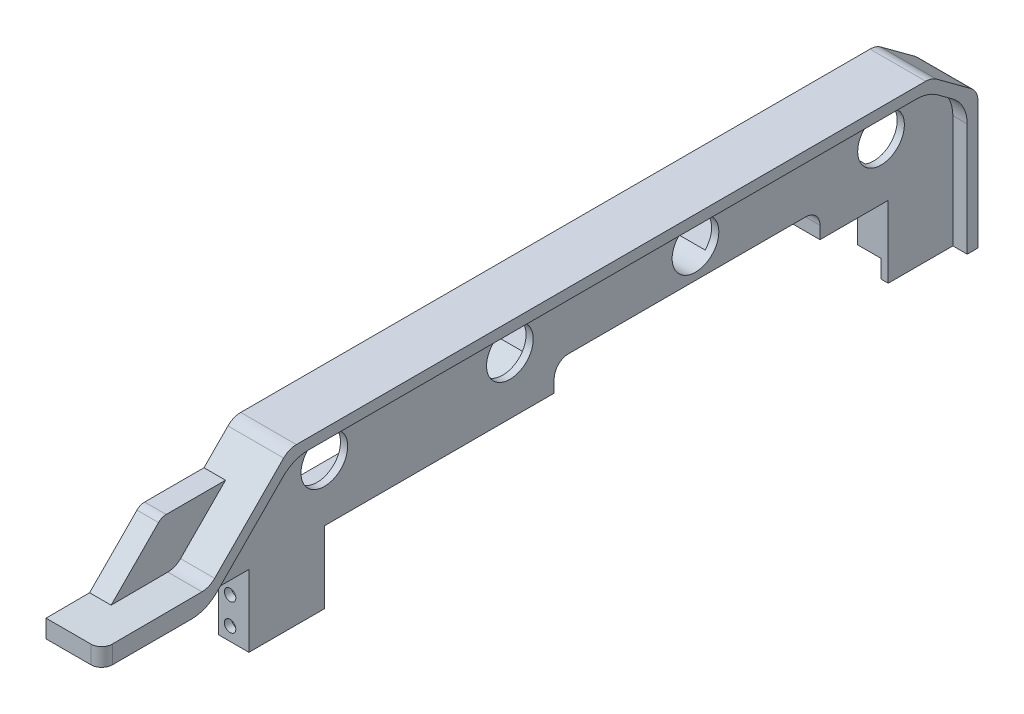
SolidWorks part; units mm, degrees
ref_plane "Front Plane" through (0, 0, 0) normal (0, 0, 1) x (1, 0, 0)
ref_plane "Top Plane" through (0, 0, 0) normal (0, 1, 0) x (1, 0, 0)
ref_plane "Right Plane" through (0, 0, 0) normal (1, 0, 0) x (0, 0, -1)
sketch "Sketch1" plane through (0, 0, 0) normal (1, 0, 0) x (0, 0, -1)
  line L0 (0, 0) -> (-130, 0)
  line L1 (0, 0) -> (74, 0) construction
  line L2 (0, 0) -> (0, 7.5)
  line L3 (0, 7.5) -> (74, 7.5)
  line L4 (74, 7.5) -> (74, 0)
  line L5 (74, 0) -> (114, 0)
  line L6 (-130, 0) -> (-130, 5)
  line L7 (-130, 5) -> (-100.0004, 5.1483)
  line L8 (-100.0004, 5.1483) -> (-77.8685, 27.5)
  line L9 (114, 0) -> (114, 18)
  line L10 (114, 18) -> (101.0882, 27.5)
  line L11 (101.0882, 27.5) -> (-77.8685, 27.5)
  dimension "D1" = 130
  dimension "D2" = 74
  dimension "D3" = 7.5
  dimension "D4" = 40
  dimension "D5" = 30
  dimension "D6" = 5
  dimension "D7" = 135
  dimension "D8" = 20
  dimension "D9" = 18
extrude "Boss-Extrude1" add sketch "Sketch1" along normal blind 25
sketch "Sketch4" plane through (25, 0, 0) normal (1, 0, 0) x (0, 0, -1)
  line L11 (-130, 0) -> (0, 0) construction
  line L12 (-130, 0) -> (0, 0) construction
  line L13 (-100.8762, 0) -> (0, 0)
  line L14 (0, 0) -> (111, 0)
  line L15 (74, 0) -> (114, 0) construction
  line L16 (111, 0) -> (111, 3)
  line L22 (-3, 3) -> (-3, 10.5)
  line L23 (-3, 10.5) -> (77, 10.5)
  line L24 (77, 10.5) -> (77, 3)
  line L25 (77, 3) -> (111, 3)
  line L26 (111, 3) -> (111, 16.4828)
  line L27 (111, 16.4828) -> (100.1035, 24.5)
  line L28 (100.1035, 24.5) -> (-76.6172, 24.5)
  line L29 (-76.6172, 24.5) -> (-97.9057, 3)
  line L30 (-97.9057, 3) -> (-3, 3)
  line L35 (111, 3) -> (111, 16.4828)
  line L36 (111, 16.4828) -> (100.1035, 24.5)
  line L37 (100.1035, 24.5) -> (-76.6172, 24.5)
  line L38 (-76.6172, 24.5) -> (-100.8762, 0)
  dimension "D1" = 3
extrude "Cut-Extrude1" cut sketch "Sketch4" against normal blind 4
ref_plane "Plane1" through (12.5, 0, 0) normal (1, 0, 0) x (0, 0, -1)
mirror "Mirror2" about plane through (12.5, 0, 0) normal (1, 0, 0) of "Cut-Extrude1"
fillet "Fillet1" radius 4 2 edges at (12.5, 7.5, -74) (12.5, 7.5, 0)
fillet "Fillet2" radius 10 8 edges at (23, 16.4828, -111) (23, 24.5, -100.1035) (2, 16.4828, -111) (2, 24.5, -100.1035) (2, 24.5, 76.6172) (23, 24.5, 76.6172) (2, 0, 100.8762) (23, 0, 100.8762)
fillet "Fillet3" radius 5 4 edges at (12.5, 18, -114) (12.5, 27.5, -101.0882) (12.5, 27.5, 77.8685) (12.5, 5.1483, 100.0004)
fillet "Fillet4" radius 3 2 edges at (0, 2.5, 130) (25, 2.5, 130)
sketch "Sketch5" plane through (12.5, 0, 0) normal (1, 0, 0) x (0, 0, -1)
  line L0 (-117.866, 5.06) -> (-103.7939, 19.2718)
  line L1 (-102.0714, 5.138) -> (-127, 5.0148) construction
  line L2 (-79.3359, 26.018) -> (-98.5432, 6.62) construction
  line L3 (-103.7939, 19.2718) -> (-72.6053, 19.2718)
  line L4 (-117.866, 5.06) -> (-95.866, 5.06)
  line L5 (-79.552, 21.536) -> (-97.9414, 2.964) construction
  line L6 (-72.6053, 19.2718) -> (-95.866, 5.06)
  dimension "D1" = 22
  dimension "D2" = 20
extrude "Boss-Extrude2" add sketch "Sketch5" along normal blind 3 and the other way blind 3
fillet "Fillet5" radius 3 1 edges at (12.5, 19.2718, 103.7939)
sketch "Sketch6" plane through (0, 0, 0) normal (0, -1, 0) x (1, 0, 0)
  line L1 (0, -111) -> (0, -114) construction
  line L2 (0, -111) -> (4, -111)
  line L3 (0, -111) -> (0, -114)
  line L4 (0, -114) -> (25, -114)
  line L5 (25, -111) -> (25, -114)
  line L6 (0, -111) -> (25, -114) construction
  line L7 (0, -114) -> (25, -111) construction
  line L8 (4, -111) -> (0, -111) construction
  line L9 (25, -114) -> (0, -114) construction
  line L10 (4, -74) -> (4, -111) construction
  line L11 (4, -111) -> (21, -111) construction
  line L12 (4, -111) -> (4, -93)
  line L13 (4, -93) -> (21, -93)
  line L14 (21, -111) -> (21, -93)
  line L15 (4, -111) -> (21, -93) construction
  line L16 (4, -93) -> (21, -111) construction
  line L17 (21, -74) -> (21, -111) construction
  line L18 (4, -111) -> (21, -111) construction
  line L19 (21, -111) -> (25, -111)
  line L21 (19, -95) -> (6, -95)
  line L22 (19, -95) -> (19, -109)
  line L23 (19, -109) -> (6, -109)
  line L24 (6, -95) -> (6, -109)
  line L25 (19, -95) -> (6, -109) construction
  line L26 (19, -109) -> (6, -95) construction
  point P6 (12.5, -112.5)
  point P16 (12.5, -102)
  point P21 (12.5, -102)
  dimension "D1" = 18
  dimension "D2" = 2
  dimension "D3" = 2
extrude "Boss-Extrude3" add sketch "Sketch6" along normal blind 20
sketch "Sketch7" plane through (0, -20, 0) normal (0, -1, 0) x (1, 0, 0)
  line L0 (19, -109) -> (19, -95) construction
  line L1 (19, -95) -> (6, -95)
  line L2 (19, -95) -> (19, -93)
  line L3 (19, -93) -> (6, -93)
  line L4 (6, -95) -> (6, -93)
  line L5 (19, -95) -> (6, -93) construction
  line L6 (19, -93) -> (6, -95) construction
  line L7 (19, -95) -> (6, -95) construction
  line L8 (21, -93) -> (4, -93) construction
  line L9 (6, -95) -> (6, -109) construction
  point P4 (12.5, -94)
sketch "Sketch8" plane through (0, 0, 0) normal (0, -1, 0) x (1, 0, 0)
  line L5 (21, 85) -> (21, 130) construction
  line L6 (21, 105.0473) -> (21, 0) construction
  line L8 (22, 130) -> (3, 130) construction
  line L9 (4, 105.0473) -> (4, 0) construction
  line L10 (21, 85) -> (4, 85)
  line L11 (21, 85) -> (21, 64)
  line L12 (21, 64) -> (19, 64)
  line L13 (4, 85) -> (4, 64)
  line L14 (21, 85) -> (4, 64) construction
  line L15 (21, 64) -> (4, 85) construction
  line L16 (19, 64) -> (6, 64) construction
  line L17 (6, 64) -> (19, 64) construction
  line L18 (6, 64) -> (6, 83)
  line L19 (6, 83) -> (19, 83)
  line L20 (19, 64) -> (19, 83)
  line L21 (6, 64) -> (19, 83) construction
  line L22 (6, 83) -> (19, 64) construction
  line L23 (6, 64) -> (4, 64)
  point P9 (12.5, 74.5)
  point P16 (12.5, 73.5)
  dimension "D1" = 45
  dimension "D2" = 21
  dimension "D3" = 2
  dimension "D4" = 2
  dimension "D5" = 2
extrude "Boss-Extrude4" add sketch "Sketch8" along normal blind 20
sketch "Sketch9" plane through (0, 0, 0) normal (0, -1, 0) x (1, 0, 0)
  line L0 (6, 64) -> (6, 83) construction
  line L1 (6, 64) -> (19, 64)
  line L2 (6, 64) -> (6, 66)
  line L3 (6, 66) -> (19, 66)
  line L4 (19, 64) -> (19, 66)
  line L5 (6, 64) -> (19, 66) construction
  line L6 (6, 66) -> (19, 64) construction
  line L7 (19, 83) -> (19, 64) construction
  point P4 (12.5, 65)
  dimension "D1" = 2
extrude "Boss-Extrude5" add sketch "Sketch9" along normal blind 8
extrude "Cut-Extrude2" cut sketch "Sketch7" against normal blind 5 contours L3 L4 L1 L2
sketch "Sketch11" plane through (0, 0, -114) normal (0, 0, -1) x (-1, 0, 0)
  line L0 (0, -20) -> (0, -12.5) construction
  line L1 (0, -20) -> (-25, -20) construction
  line L2 (0, -20) -> (0, 15.4713) construction
  line L3 (0, -16.25) -> (-25, -16.25) construction
  line L4 (-25, -20) -> (-25, 15.4713) construction
  line L5 (0, -16.25) -> (-9.25, -16.25) construction
  line L6 (-12.5, -20) -> (-12.5, -5) construction
  line L7 (0, -20) -> (0, -16.25)
  line L8 (-25, -20) -> (-25, -12.5) construction
  line L9 (-25, -12.5) -> (0, -12.5) construction
  circle A0 centre (-9.25, -16.25) radius 1.6
  circle A1 centre (-15.75, -16.25) radius 1.6
  circle A2 centre (-15.75, -8.75) radius 1.6
  circle A3 centre (-9.25, -8.75) radius 1.6
  circle A4 centre (-15.75, -16.25) radius 3 construction
  dimension "D2" = 3.2
  dimension "D5" = 6
  dimension "D1" = 9.25
  dimension "D3" = 3.75
  dimension "D4" = 7.5
extrude "Cut-Extrude3" cut sketch "Sketch11" against normal up to surface (19 mm away) contours A1 | A2 | A3 | A0 up to face at (12.5, -7.5, -95)
sketch "Sketch12" plane through (0, 0, 85) normal (0, 0, 1) x (1, 0, 0)
  line L0 (15.75, -8.75) -> (21, -8.75) construction
  line L1 (15.75, -8.75) -> (15.75, -5) construction
  line L3 (12.5, -20) -> (12.5, -5) construction
  line L6 (0, -12.5) -> (25, -12.5) construction
  line L7 (4, -20) -> (21, -20) construction
  line L8 (4, -20) -> (4, 0) construction
  line L9 (21, -20) -> (21, 0) construction
  circle A0 centre (15.75, -16.25) radius 1.6
  circle A1 centre (9.25, -16.25) radius 1.6
  circle A2 centre (9.25, -8.75) radius 1.6
  circle A3 centre (15.75, -8.75) radius 1.6
  circle A4 centre (9.25, -16.25) radius 3 construction
  dimension "D1" = 3.2
  dimension "D2" = 5.25
  dimension "D3" = 3.75
extrude "Cut-Extrude4" cut sketch "Sketch12" against normal up to surface (2 mm away) up to face at (12.5, -10, 83)
sketch "Sketch14" plane through (12.5, 0, 0) normal (1, 0, 0) x (0, 0, -1)
  line L0 (-83, 0) -> (-83, 13.4752)
  line L1 (-66, 0) -> (-66, 4)
  line L2 (-66, 4) -> (-13.3251, 4)
  line L3 (-13.3251, 4) -> (-5.8251, 11.5)
  line L4 (-5.8251, 11.5) -> (87.0794, 11.5)
  line L5 (95, 0) -> (95, 3.5794)
  line L6 (95, 3.5794) -> (87.0794, 11.5)
  line L7 (109, 0) -> (109, 10.0924)
  line L8 (109, -20) -> (109, 0) construction
  line L9 (95, 0) -> (109, 0) construction
  line L10 (109, 10.0924) -> (95.5924, 23.5)
  line L15 (-72.9752, 23.5) -> (-83, 13.4752)
  line L16 (-83, 0) -> (-66, 0)
  line L17 (95, 0) -> (109, 0)
  line L18 (95.5924, 23.5) -> (-72.9752, 23.5)
  line L19 (-64, 0) -> (0, 0) construction
  line L20 (99.447, 27.5) -> (-75.783, 27.5) construction
  line L21 (70, 7.5) -> (4, 7.5) construction
  dimension "D1" = 135
  dimension "D2" = 135
  dimension "D3" = 135
  dimension "D4" = 135
  dimension "D5" = 4
  dimension "D6" = 4
  dimension "D7" = 4
extrude "Cut-Extrude5" cut sketch "Sketch14" against normal blind 6.5 and the other way blind 6.5
sketch "Sketch15" plane through (4, 0, 0) normal (-1, 0, 0) x (0, 0, 1)
  line L0 (-37, 7.5) -> (-37, 24.5) construction
  line L1 (-70, 7.5) -> (-4, 7.5) construction
  line L2 (-96.8211, 24.5) -> (72.4461, 24.5) construction
  line L3 (-37, 16) -> (-111, 16) construction
  line L4 (-37, 16) -> (84, 16) construction
  line L6 (-111, 16) -> (-13.5, 16) construction
  line L7 (-13.5, 16) -> (-13.5, 7.5) construction
  line L8 (-111, 16) -> (-91, 16) construction
  circle A1 centre (-91, 16) radius 6.5
  circle A2 centre (-39.3333, 16) radius 6.5
  circle A3 centre (64, 16) radius 6.5
  circle A4 centre (12.3333, 16) radius 6.5
  dimension "D5" = 13
  dimension "D1" = 74
  dimension "D2" = 121
  dimension "D3" = 97.5
  dimension "D4" = 20
  dimension "D6" = 51.6667
extrude "large screw holes" cut sketch "Sketch15" against normal up to surface (17 mm away)
sketch "Sketch17" plane through (0, 27.5, 0) normal (0, 1, 0) x (1, 0, 0)
  line L1 (0, 129.4943) -> (9.5, 129.4943)
  line L2 (0, 129.4943) -> (0, -133.4944)
  line L3 (0, -133.4944) -> (9.5, -133.4944)
  line L4 (9.5, 129.4943) -> (9.5, -133.4944)
  line L5 (0, 129.4943) -> (9.5, -133.4944) construction
  line L6 (0, -133.4944) -> (9.5, 129.4943) construction
  line L7 (9.5, -86.0157) -> (9.5, -102.5426) construction
  point P4 (4.75, -2)
  point P6 (9.5, -117.866)
  point P11 (9.5, -117.866)
extrude "Cut-Extrude6" cut sketch "Sketch17" against normal through all
sketch "Sketch18" plane through (0, 0, 85) normal (0, 0, 1) x (1, 0, 0)
  line L0 (12.5, -26.125) -> (12.5, 26.125) construction
  line L1 (9.5, 0) -> (12.5, 0)
  line L2 (9.5, 0) -> (9.5, -20)
  line L3 (9.5, -20) -> (12.5, -20)
  line L4 (12.5, 0) -> (12.5, -20)
  line L5 (9.5, 0) -> (12.5, -20) construction
  line L6 (9.5, -20) -> (12.5, 0) construction
  line L7 (21, -20) -> (9.5, -20) construction
  point P4 (11, -10)
extrude "Cut-Extrude7" cut sketch "Sketch18" against normal through all
